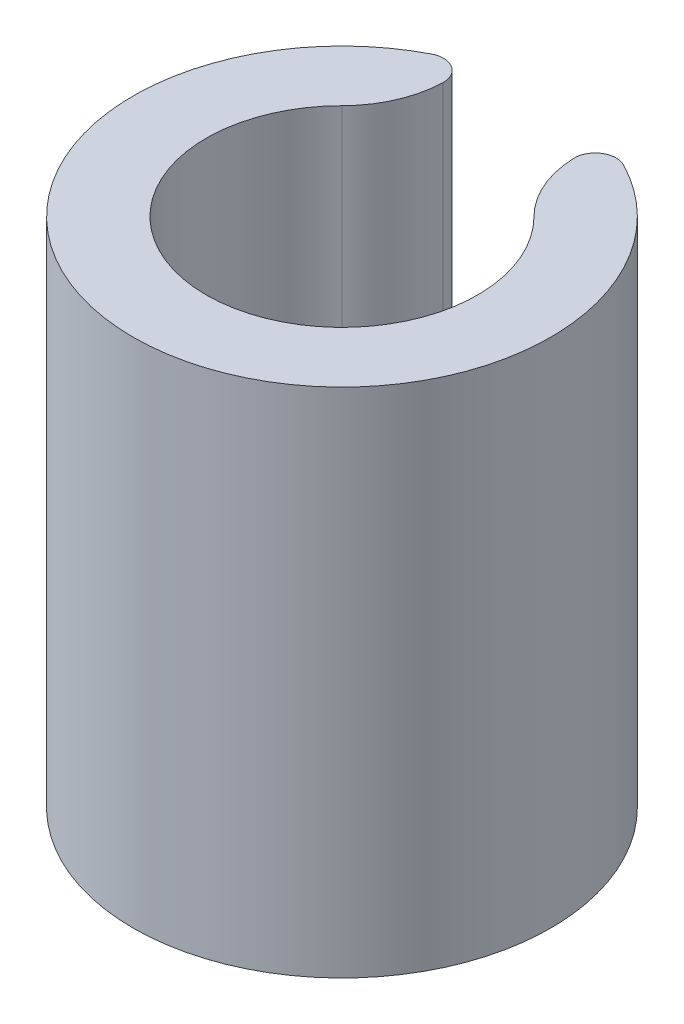
SolidWorks part; units mm, degrees
ref_plane "Front" through (0, 0, 0) normal (0, 0, 1) x (1, 0, 0)
ref_plane "Top" through (0, 0, 0) normal (0, 1, 0) x (1, 0, 0)
ref_plane "Right" through (0, 0, 0) normal (1, 0, 0) x (0, 0, -1)
sketch "Sketch1" plane through (0, 0, 0) normal (0, 1, 0) x (1, 0, 0)
  circle A0 centre (0, 0) radius 2.6
  circle A1 centre (0, 0) radius 4
  dimension "D1" = 5.2
  dimension "8" = 8
extrude "Boss-Extrude1" add sketch "Sketch1" along normal blind 9.8
sketch "Sketch2" plane through (0, 9.8, 0) normal (0, 1, 0) x (1, 0, 0)
  line L0 (-2.6, 0) -> (-2.6, 5.0408) construction
  line L1 (2.6, 0) -> (2.6, 5.0408) construction
  line L2 (0, 0) -> (-1.8385, 1.8385) construction
  line L3 (0, 0) -> (1.8385, 1.8385) construction
  line L4 (0, 0) -> (0, 0.935) construction
  line L5 (-1.2527, 3.2527) -> (1.2527, 3.2527) construction
  circle A0 centre (0, 0) radius 2.6 construction
  arc A1 (-1.8385, 1.8385) -> (-1.3221, 3.7752) centre (-3.2527, 3.2527) ccw
  circle A2 centre (0, 0) radius 4 construction
  arc A3 (1.8385, 1.8385) -> (1.3221, 3.7752) centre (3.2527, 3.2527) cw
  arc A5 (-1.8385, 1.8385) -> (1.8385, 1.8385) centre (0, 0) cw
  arc A6 (-1.3221, 3.7752) -> (1.3221, 3.7752) centre (0, 0) cw
  dimension "D3" = 2
  dimension "D2" = 2.5054
  dimension "D1" = 45
extrude "Cut-Extrude1" cut sketch "Sketch2" against normal through all
fillet "Fillet1" radius 0.4 2 edges at (1.3221, 4.9, -3.7752) (-1.3221, 4.9, -3.7752)
